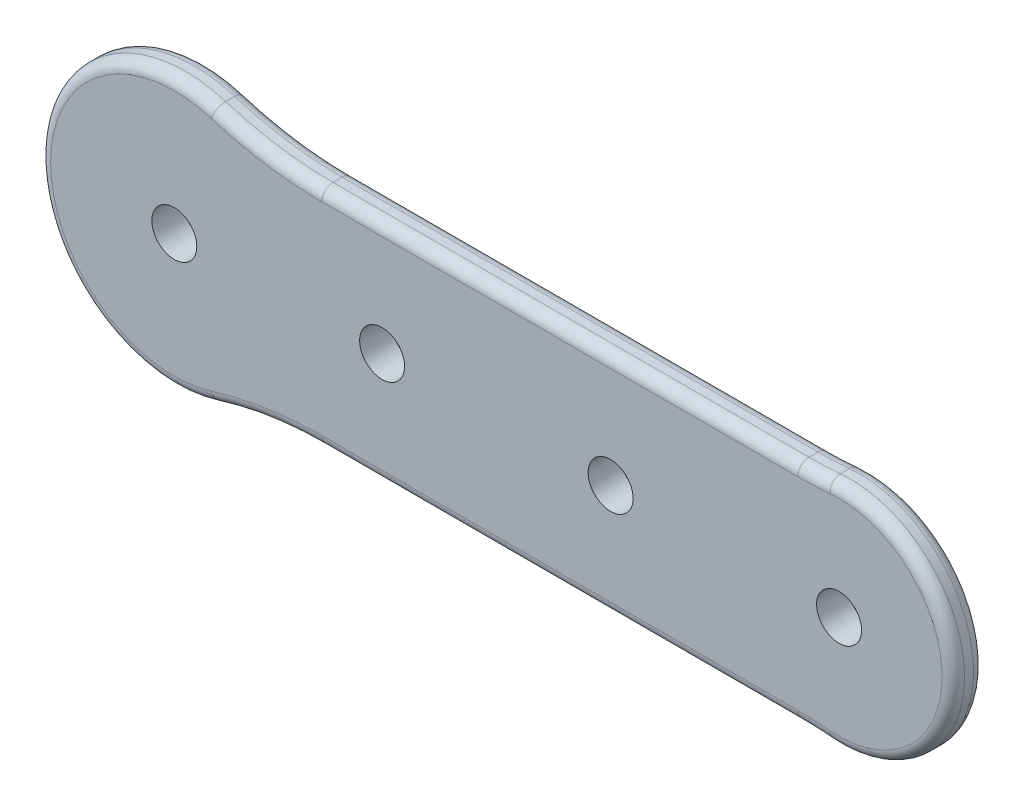
SolidWorks part; units mm, degrees
material "Plain Carbon Steel"
ref_plane "Front Plane" through (0, 0, 0) normal (0, 0, 1) x (1, 0, 0)
ref_plane "Top Plane" through (0, 0, 0) normal (0, 1, 0) x (1, 0, 0)
ref_plane "Right Plane" through (0, 0, 0) normal (1, 0, 0) x (0, 0, -1)
sketch "Sketch1" plane through (0, 0, 0) normal (0, 0, 1) x (1, 0, 0)
  line L1 (-73.9, 25) -> (73.9, 25)
  line L2 (-73.9, 25) -> (-73.9, -25)
  line L3 (-73.9, -25) -> (73.9, -25)
  line L4 (73.9, 25) -> (73.9, -25)
  line L5 (-73.9, 25) -> (73.9, -25) construction
  line L6 (-73.9, -25) -> (73.9, 25) construction
  circle A0 centre (-73.9, 0) radius 30
  circle A1 centre (73.9, 0) radius 25.4
  circle A2 centre (73.9, 0) radius 5
  circle A3 centre (-73.9, 0) radius 5
  circle A4 centre (23.1, 0) radius 5
  circle A5 centre (-27.7, 0) radius 5
  point P0 (0, 0)
  point P10 (99.3, 0)
  point P11 (-103.9, 0)
  dimension "D1" = 50.8
  dimension "D2" = 60
  dimension "D5" = 50.8
  dimension "D6" = 50.8
  dimension "D7" = 10
  dimension "D8" = 10
  dimension "D9" = 10
  dimension "D10" = 10
  dimension "D3" = 50
  dimension "D4" = 203.2
extrude "Boss-Extrude1" add sketch "Sketch1" along normal blind 7 contours A1 L1 A0 L3 A5 A4 | A2 L4 L3 A1 L1 | A2 L4 L1 A1 L3 | A3 L2 L3 A0 L1 | A3 L2 L1 A0 L3
fillet "Fillet1" radius 80 4 edges at (69.41, -25, 3.5) (69.41, 25, 3.5) (-57.3169, -25, 3.5) (-57.3169, 25, 3.5)
fillet "Fillet2" radius 2.5 16 edges at (-53.1733, 25.9143, 7) (-53.1733, 25.9143, 0) (-103.9, 0, 0) (-103.9, 0, 7) (-53.1733, -25.9143, 7) (-53.1733, -25.9143, 0) (11.8067, -25, 0) (11.8067, -25, 7) (68.211, -25.0759, 7) (68.211, -25.0759, 0) (99.3, 0, 7) (99.3, 0, 0) (68.211, 25.0759, 7) (68.211, 25.0759, 0) (11.8067, 25, 7) (11.8067, 25, 0)
